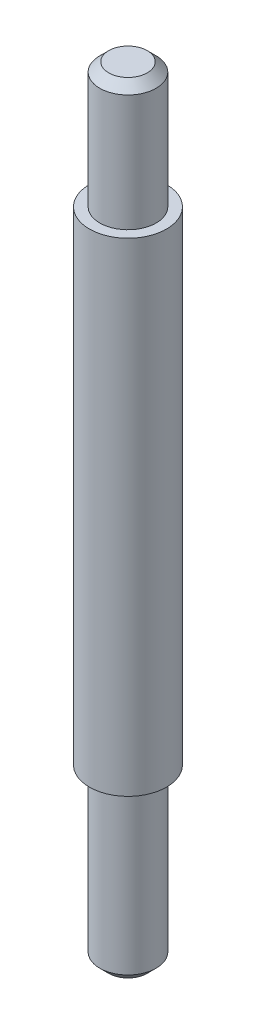
SolidWorks part; units mm, degrees
ref_plane "Front Plane" through (0, 0, 0) normal (0, 0, 1) x (1, 0, 0)
ref_plane "Top Plane" through (0, 0, 0) normal (0, 1, 0) x (1, 0, 0)
ref_plane "Right Plane" through (0, 0, 0) normal (1, 0, 0) x (0, 0, -1)
sketch "Sketch1" plane through (0, 0, 0) normal (1, 0, 0) x (0, 0, -1)
  line L0 (0, 1.4) -> (0, -1.23) construction
  line L1 (-0.4244, 0) -> (0.452, 0) construction
  line L2 (0, 1.4) -> (-0.065, 1.4)
  line L3 (-0.095, 1.37) -> (-0.095, 0.9764)
  line L4 (-0.095, 0.9764) -> (-0.13, 0.9764)
  line L5 (-0.13, 0.9764) -> (-0.13, -0.6536)
  line L6 (-0.13, -0.6536) -> (-0.095, -0.6536)
  line L7 (-0.095, -0.6536) -> (-0.095, -1.2)
  line L8 (-0.065, -1.23) -> (0, -1.23)
  line L9 (-0.065, 1.4) -> (-0.095, 1.37)
  line L10 (-0.095, -1.2) -> (-0.065, -1.23)
  line L11 (0, 1.4) -> (0, -1.23)
  point P5 (0, 0)
  point P6 (-0.095, 1.4)
  point P11 (-0.095, -1.23)
  point P16 (0.452, 0)
  point P17 (-0.4244, 0)
  dimension "D1" = 2.63
  dimension "D2" = 1.63
  dimension "D3" = 0.19
  dimension "D4" = 0.03
  dimension "D5" = 0.26
  dimension "D6" = 0.03
  dimension "D7" = 0.03
  dimension "D8" = 0.03
revolve "Revolve1" add sketch "Sketch1" angle 360 about L11
